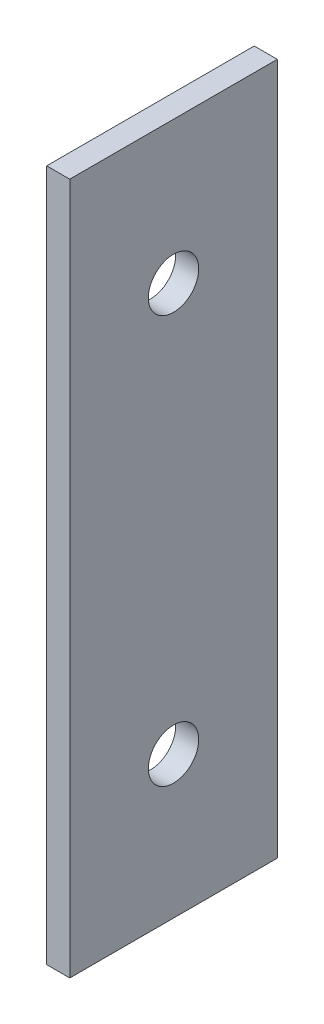
SolidWorks part; units mm, degrees
ref_plane "Front Plane" through (0, 0, 0) normal (0, 0, 1) x (1, 0, 0)
ref_plane "Top Plane" through (0, 0, 0) normal (0, 1, 0) x (1, 0, 0)
ref_plane "Right Plane" through (0, 0, 0) normal (1, 0, 0) x (0, 0, -1)
sketch "Sketch1" plane through (0, 0, 0) normal (0, 0, 1) x (1, 0, 0)
  line L1 (2.1292, 7.0575) -> (3.1292, 7.0575)
  line L2 (2.1292, 7.0575) -> (2.1292, -22.9425)
  line L3 (2.1292, -22.9425) -> (3.1292, -22.9425)
  line L4 (3.1292, 7.0575) -> (3.1292, -22.9425)
  line L10 (3.1292, -4.9425) -> (3.1292, -22.9425)
  dimension "D1" = 30
  dimension "D3" = 1
extrude "Boss-Extrude1" add sketch "Sketch1" along normal blind 9
sketch "Sketch2" plane through (3.1292, 0, 0) normal (1, 0, 0) x (0, 0, -1)
  line L0 (-4.5, 7.0575) -> (-4.5, -22.9425) construction
  line L1 (-9, 7.0575) -> (0, 7.0575) construction
  line L2 (-9, -22.9425) -> (0, -22.9425) construction
  line L3 (-9, 7.0575) -> (-9, -22.9425) construction
  line L4 (0, -7.9425) -> (-9, -7.9425) construction
  line L5 (0, 7.0575) -> (0, -22.9425) construction
  circle A0 centre (-4.5, 0.8975) radius 1.0922
  circle A1 centre (-4.5, -16.7825) radius 1.0922
  dimension "D1" = 2.1844
  dimension "D2" = 17.68
  dimension "D3" = 6.16
extrude "Cut-Extrude1" cut sketch "Sketch2" against normal blind 10
